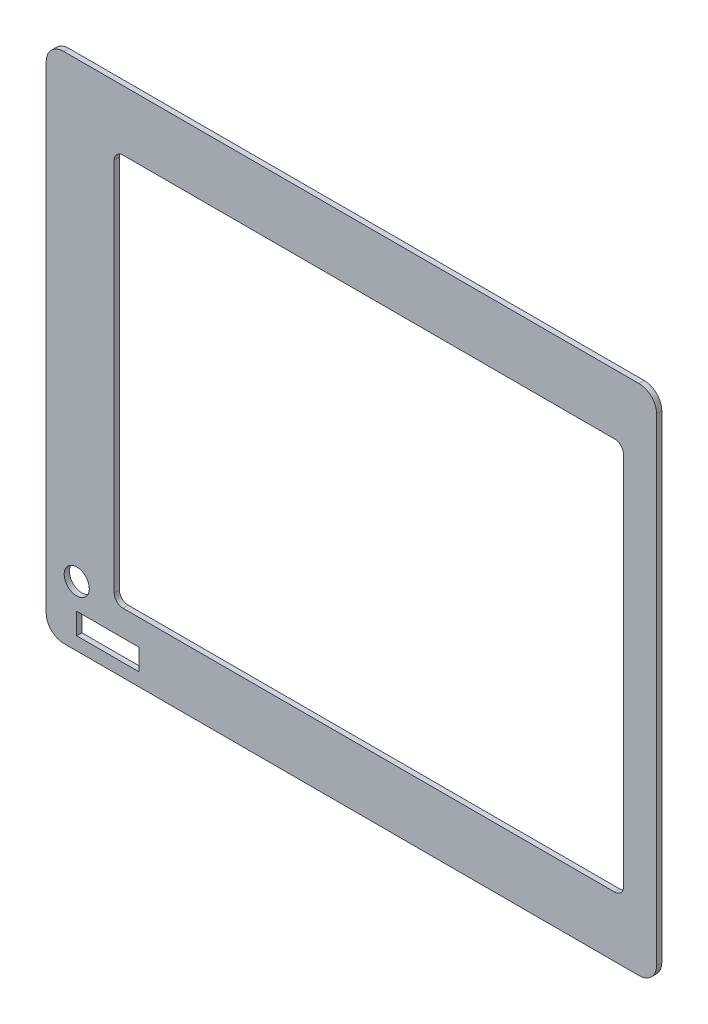
SolidWorks part; units mm, degrees
ref_plane "Front Plane" through (0, 0, 0) normal (0, 0, 1) x (1, 0, 0)
ref_plane "Top Plane" through (0, 0, 0) normal (0, 1, 0) x (1, 0, 0)
ref_plane "Right Plane" through (0, 0, 0) normal (1, 0, 0) x (0, 0, -1)
sketch "Sketch1" plane through (0, 0, 0) normal (0, 0, 1) x (1, 0, 0)
  line L1 (-350, -294) -> (350, -294)
  line L2 (-350, -294) -> (-350, 294)
  line L3 (-350, 294) -> (350, 294)
  line L4 (350, -294) -> (350, 294)
  line L5 (-350, -294) -> (350, 294) construction
  line L6 (-350, 294) -> (350, -294) construction
  point P0 (0, 0)
  dimension "D1" = 588
  dimension "D2" = 700
extrude "Boss-Extrude1" add sketch "Sketch1" along normal blind 6
fillet "Fillet1" radius 20 4 edges at (-350, 294, 3) (350, 294, 3) (350, -294, 3) (-350, -294, 3)
sketch "Sketch2" plane through (0, 0, 6) normal (0, 0, 1) x (1, 0, 0)
  line L0 (-350, 274) -> (-350, -274) construction
  line L138 (330, 294) -> (-330, 294) construction
  line L139 (-330, -294) -> (330, -294) construction
  line L144 (-315, -279) -> (-243.7, -279)
  line L151 (-315, -279) -> (-315, -254.6)
  line L152 (-315, -254.6) -> (-243.7, -254.6)
  line L153 (-243.7, -279) -> (-243.7, -254.6)
  line L154 (-262, -225) -> (302, -225)
  line L155 (-272, -215) -> (-272, 215)
  line L156 (-262, 225) -> (302, 225)
  line L157 (312, -215) -> (312, 215)
  line L163 (188.4646, -283.6) -> (311, -283.6)
  line L168 (-320.35, -283.6) -> (-238.35, -283.6)
  line L169 (-320.35, -283.6) -> (-320.35, -249.6)
  line L170 (-320.35, -249.6) -> (-238.35, -249.6)
  line L171 (-238.35, -283.6) -> (-238.35, -249.6)
  line L172 (-320.35, -283.6) -> (-238.35, -249.6) construction
  line L173 (-320.35, -249.6) -> (-238.35, -283.6) construction
  arc A75 (302, 225) -> (312, 215) centre (302, 215) cw
  arc A76 (-272, 215) -> (-262, 225) centre (-262, 215) cw
  arc A77 (302, -225) -> (312, -215) centre (302, -215) ccw
  arc A78 (-262, -225) -> (-272, -215) centre (-262, -215) cw
  circle A79 centre (-315, -225) radius 14.4
  text T2 "Masteroppgave Emil Aasen Skogheim" font "Century Gothic" height in points 16
  point P226 (-279.35, -266.6)
  dimension "D17" = 450
  dimension "D26" = 71.3
  dimension "D29" = 10
  dimension "D27" = 15
  dimension "D28" = 12
  dimension "D31" = 35.65
  dimension "D30" = 28.8
  dimension "D18" = 584
  dimension "D20" = 24.4
  dimension "D32" = 35
  dimension "D33" = 82
  dimension "D34" = 34
extrude "Cut-Extrude1" cut sketch "Sketch2" against normal blind 10 contours L155 A76 L156 A75 L157 A77 L154 A78 | L151 L152 L153 L144 | A79
